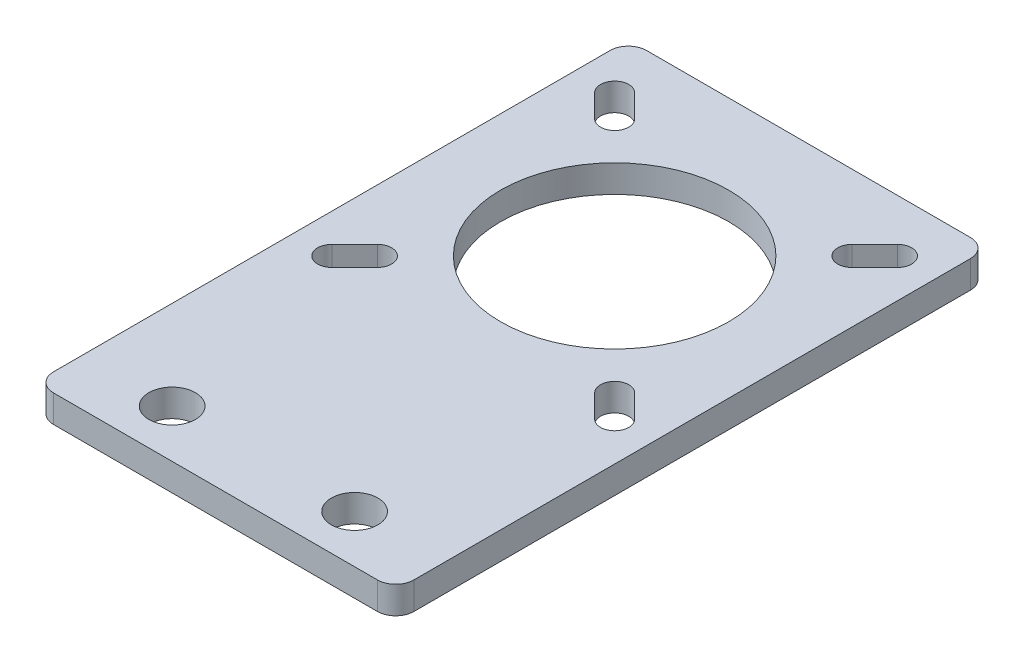
SolidWorks part; units mm, degrees
material "6061-T6 (SS)"
ref_plane "Front Plane" through (0, 0, 0) normal (0, 0, 1) x (1, 0, 0)
ref_plane "Top Plane" through (0, 0, 0) normal (0, 1, 0) x (1, 0, 0)
ref_plane "Right Plane" through (0, 0, 0) normal (1, 0, 0) x (0, 0, -1)
sketch "Sketch1" plane through (0, 0, 0) normal (0, 1, 0) x (1, 0, 0)
  line L0 (0, 0) -> (30, 0) construction
  line L1 (17.75, -43.75) -> (-17.75, -43.75)
  line L2 (19.75, -41.75) -> (19.75, 19.25)
  line L3 (17.75, 21.25) -> (-17.75, 21.25)
  line L4 (-19.75, -41.75) -> (-19.75, 19.25)
  line L5 (0, 21.25) -> (0, 0) construction
  line L6 (13, 13) -> (15.5, 15.5) construction
  line L7 (11.904, 14.096) -> (14.404, 16.596)
  line L8 (14.096, 11.904) -> (16.596, 14.404)
  line L9 (-10, -38.5) -> (10, -38.5) construction
  line L10 (-13, 13) -> (-15.5, 15.5) construction
  line L11 (-11.904, 14.096) -> (-14.404, 16.596)
  line L12 (-14.096, 11.904) -> (-16.596, 14.404)
  line L13 (-13, -13) -> (-15.5, -15.5) construction
  line L14 (-11.904, -14.096) -> (-14.404, -16.596)
  line L15 (-14.096, -11.904) -> (-16.596, -14.404)
  line L16 (13, -13) -> (15.5, -15.5) construction
  line L17 (11.904, -14.096) -> (14.404, -16.596)
  line L18 (14.096, -11.904) -> (16.596, -14.404)
  line L19 (0, 0) -> (0, -28.5) construction
  line L22 (0, 0) -> (27.1737, 27.1737) construction
  arc A0 (-17.75, -43.75) -> (-19.75, -41.75) centre (-17.75, -41.75) cw
  arc A1 (17.75, -43.75) -> (19.75, -41.75) centre (17.75, -41.75) ccw
  arc A2 (19.75, 19.25) -> (17.75, 21.25) centre (17.75, 19.25) ccw
  arc A3 (-17.75, 21.25) -> (-19.75, 19.25) centre (-17.75, 19.25) ccw
  circle A4 centre (0, 0) radius 12.5
  arc A5 (11.904, 14.096) -> (14.096, 11.904) centre (13, 13) ccw
  arc A6 (16.596, 14.404) -> (14.404, 16.596) centre (15.5, 15.5) ccw
  circle A8 centre (10, -38.5) radius 2.55
  circle A12 centre (-10, -38.5) radius 2.55
  arc A13 (-11.904, 14.096) -> (-14.096, 11.904) centre (-13, 13) cw
  arc A14 (-16.596, 14.404) -> (-14.404, 16.596) centre (-15.5, 15.5) cw
  arc A15 (-11.904, -14.096) -> (-14.096, -11.904) centre (-13, -13) ccw
  arc A16 (-16.596, -14.404) -> (-14.404, -16.596) centre (-15.5, -15.5) ccw
  arc A17 (11.904, -14.096) -> (14.096, -11.904) centre (13, -13) cw
  arc A18 (16.596, -14.404) -> (14.404, -16.596) centre (15.5, -15.5) cw
  circle A19 centre (0, -38.5) radius 2.55 [skipped]
  point P4 (14.25, 14.25)
  point P23 (0, -38.5)
  point P24 (0, 0)
  point P40 (-14.25, 14.25)
  point P47 (-14.25, -14.25)
  point P54 (14.25, -14.25)
  dimension "D2" = 2
  dimension "D3" = 21.25
  dimension "D5" = 3.1
  dimension "D7" = 10
  dimension "D10" = 3
  dimension "D4" = 25
  dimension "D14" = 8.25
  dimension "D15" = 28.5
  dimension "D6" = 20
  dimension "D1" = 65
  dimension "D9" = 39.5
  dimension "D13" = 5.75
  dimension "D16" = 45
extrude "Boss-Extrude1" add sketch "Sketch1" along normal blind 3
